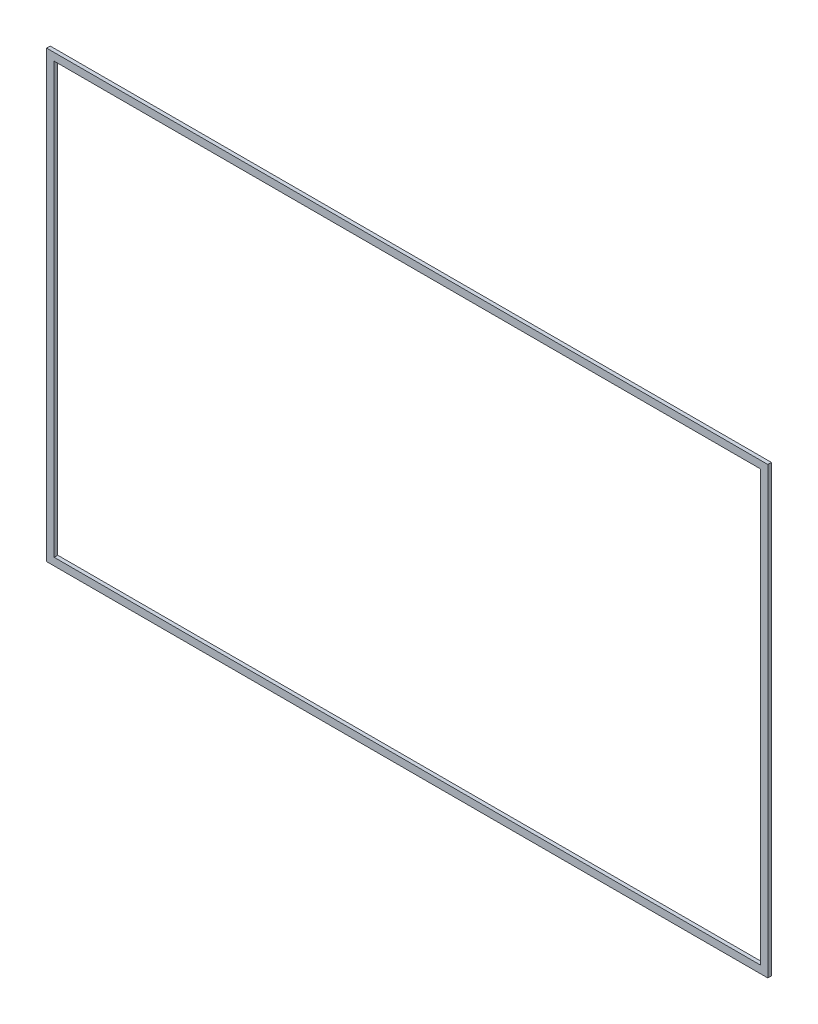
SolidWorks part; units mm, degrees
material "Rubber"
ref_plane "Front Plane" through (0, 0, 0) normal (0, 0, 1) x (1, 0, 0)
ref_plane "Top Plane" through (0, 0, 0) normal (0, 1, 0) x (1, 0, 0)
ref_plane "Right Plane" through (0, 0, 0) normal (1, 0, 0) x (0, 0, -1)
sketch "Sketch1" plane through (0, 0, 0) normal (0, 0, 1) x (1, 0, 0)
  line L0 (-117.5, 71.5) -> (117.5, 71.5)
  line L1 (-120, -74) -> (120, -74)
  line L2 (-120, -74) -> (-120, 74)
  line L3 (-120, 74) -> (120, 74)
  line L4 (120, -74) -> (120, 74)
  line L5 (-120, -74) -> (120, 74) construction
  line L6 (-120, 74) -> (120, -74) construction
  line L7 (117.5, -71.5) -> (117.5, 71.5)
  line L8 (-117.5, -71.5) -> (117.5, -71.5)
  line L9 (-117.5, -71.5) -> (-117.5, 71.5)
  point P0 (0, 0)
  point P6 (120.3735, 74.0778)
  point P7 (120.0724, -74.2237)
  point P8 (0, 0)
  point P9 (120.1028, -74.254)
  point P10 (132.7377, -101.2958)
  point P11 (-120, -73.7942)
  point P13 (-120.1347, 73.5646)
  point P14 (-120.022, 73.6686)
  point P15 (119.9262, 73.9545)
  point P16 (-116.9781, -73.7132)
  point P18 (0, 0)
  point P19 (0, 0)
  dimension "D3" = 2.5
  dimension "D1" = 148
  dimension "D2" = 240
extrude "Boss-Extrude1" add sketch "Sketch1" against normal blind 1.2
